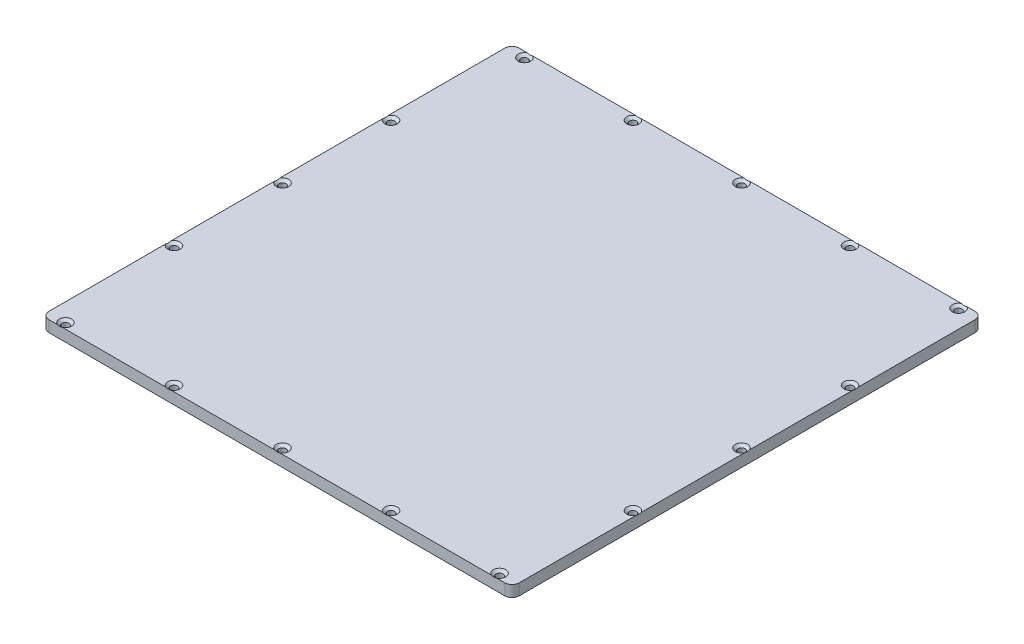
SolidWorks part; units mm, degrees
ref_plane "Front Plane" through (0, 0, 0) normal (0, 0, 1) x (1, 0, 0)
ref_plane "Top Plane" through (0, 0, 0) normal (0, 1, 0) x (1, 0, 0)
ref_plane "Right Plane" through (0, 0, 0) normal (1, 0, 0) x (0, 0, -1)
sketch "Sketch1" plane through (0, 0, 0) normal (0, 1, 0) x (1, 0, 0)
  line L1 (-82.55, -82.55) -> (82.55, -82.55)
  line L2 (-82.55, -82.55) -> (-82.55, 82.55)
  line L3 (-82.55, 82.55) -> (82.55, 82.55)
  line L4 (82.55, -82.55) -> (82.55, 82.55)
  line L5 (-82.55, -82.55) -> (82.55, 82.55) construction
  line L6 (-82.55, 82.55) -> (82.55, -82.55) construction
  point P0 (0, 0)
  dimension "D1" = 165.1
  dimension "D2" = 165.1
extrude "Boss-Extrude1" add sketch "Sketch1" against normal blind 3.9624
sketch "Sketch4" plane through (0, 0, 0) normal (0, 1, 0) x (1, 0, 0)
  line L1 (0, 82.55) -> (0, -82.55) construction
  line L2 (82.55, 82.55) -> (-82.55, 82.55) construction
  line L3 (-82.55, -82.55) -> (82.55, -82.55) construction
  line L4 (-82.55, 0) -> (82.55, 0) construction
  line L5 (-82.55, 82.55) -> (-82.55, -82.55) construction
  line L6 (82.55, -82.55) -> (82.55, 82.55) construction
  point P12 (-80.5688, 76.2)
  point P13 (-38.1, 80.5688)
  point P14 (0, 80.5688)
  point P15 (38.1, 80.5688)
  point P16 (76.2, 80.5688)
  point P17 (-80.5688, 0)
  point P18 (-80.5688, 38.1)
  point P19 (-80.5688, -38.1)
  point P20 (-80.5688, -76.2)
  point P21 (-38.1, -80.5688)
  point P22 (-76.2, -80.5688)
  point P23 (0, -80.5688)
  point P24 (38.1, -80.5688)
  point P25 (-76.2, 80.5688)
  point P26 (76.2, -80.5688)
  point P27 (80.5688, -38.1)
  point P28 (80.5688, 0)
  point P29 (80.5688, 38.1)
  point P30 (80.5688, 76.2)
  point P32 (80.5688, -76.2)
  dimension "D1" = 6.35
  dimension "D2" = 1.9812
  dimension "D3" = 38.1
  dimension "D4" = 6.35
  dimension "D5" = 38.1
  dimension "D6" = 6.35
  dimension "D7" = 1.9812
  dimension "D8" = 38.1
  dimension "D9" = 6.35
  dimension "D10" = 38.1
  dimension "D11" = 1.9812
  dimension "D12" = 1.9812
hole_wizard "CSK for #2 Flat Head Machine Screw (100)1" positions "Sketch5" profile "Sketch7" countersink size "#2" standard "ANSI Inch" end condition through all
sketch "Sketch5" plane through (0, 0, 0) normal (0, 1, 0) x (1, 0, 0)
  point P0 (-76.2, 80.5688)
  point P6 (-80.5688, 38.1)
  point P9 (-80.5688, 0)
  point P12 (-80.5688, -38.1)
  point P18 (-76.2, -80.5688)
  point P21 (-38.1, -80.5688)
  point P24 (0, -80.5688)
  point P27 (38.1, -80.5688)
  point P37 (80.5688, -38.1)
  point P40 (80.5688, 0)
  point P43 (80.5688, 38.1)
  point P49 (76.2, 80.5688)
  point P52 (38.1, 80.5688)
  point P55 (0, 80.5688)
  point P58 (-38.1, 80.5688)
  point P61 (76.2, -80.5688)
  point P63 (76.2, -80.5688)
sketch "Sketch7" plane through (-76.2, 0, -80.5688) normal (1, 0, 0) x (0, 0, 1)
  line L0 (0, 0) -> (0, 3.9624)
  line L1 (0, 3.9624) -> (1.2192, 3.9624)
  line L2 (1.2192, 3.9624) -> (1.2192, 0.8099)
  line L3 (1.2192, 0.8099) -> (2.1844, 0)
  line L5 (2.1844, 0) -> (0, 0)
  line L6 (-1.2192, 0.8099) -> (-2.1844, 0) construction
  line L11 (0, -6.35) -> (0, 107.95) construction
  dimension "Thru Hole Dia." = 2.4384
  dimension "Thru Hole Depth" = 3.9624
  dimension "Near C'Sink Dia." = 4.3688
  dimension "Near C'Sink Angle" = 100
fillet "Fillet2" radius 2.54 4 edges at (82.55, -1.9812, 82.55) (82.55, -1.9812, -82.55) (-82.55, -1.9812, -82.55) (-82.55, -1.9812, 82.55)
